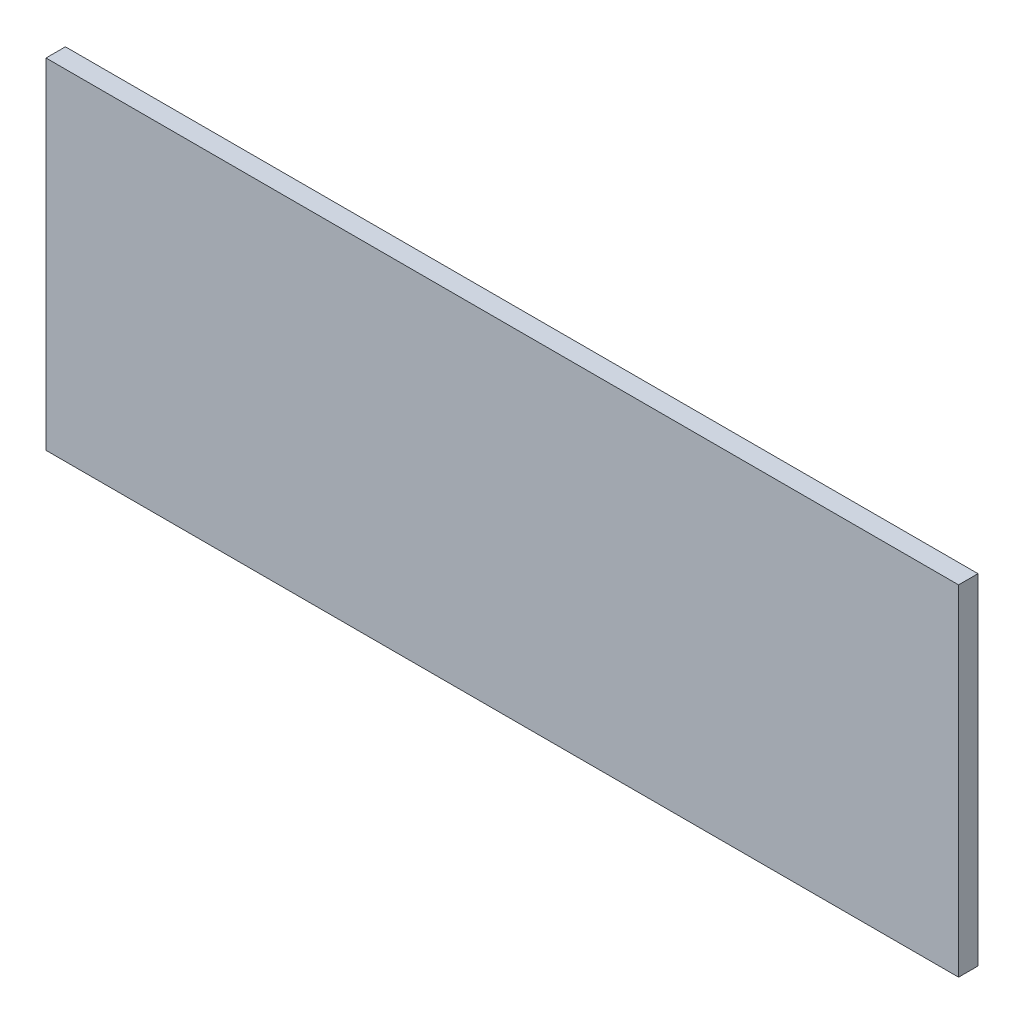
SolidWorks part; units mm, degrees
ref_plane "Plan de face" through (0, 0, 0) normal (0, 0, 1) x (1, 0, 0)
ref_plane "Plan de dessus" through (0, 0, 0) normal (0, 1, 0) x (1, 0, 0)
ref_plane "Plan de droite" through (0, 0, 0) normal (1, 0, 0) x (0, 0, -1)
sketch "Esquisse1" plane through (0, 0, 0) normal (0, 0, 1) x (1, 0, 0)
  line L1 (0, 0) -> (470, 0)
  line L2 (0, 0) -> (0, 175)
  line L3 (0, 175) -> (470, 175)
  line L4 (470, 0) -> (470, 175)
  dimension "D1" = 470
  dimension "D2" = 175
extrude "Boss.-Extru.1" add sketch "Esquisse1" along normal blind 10
